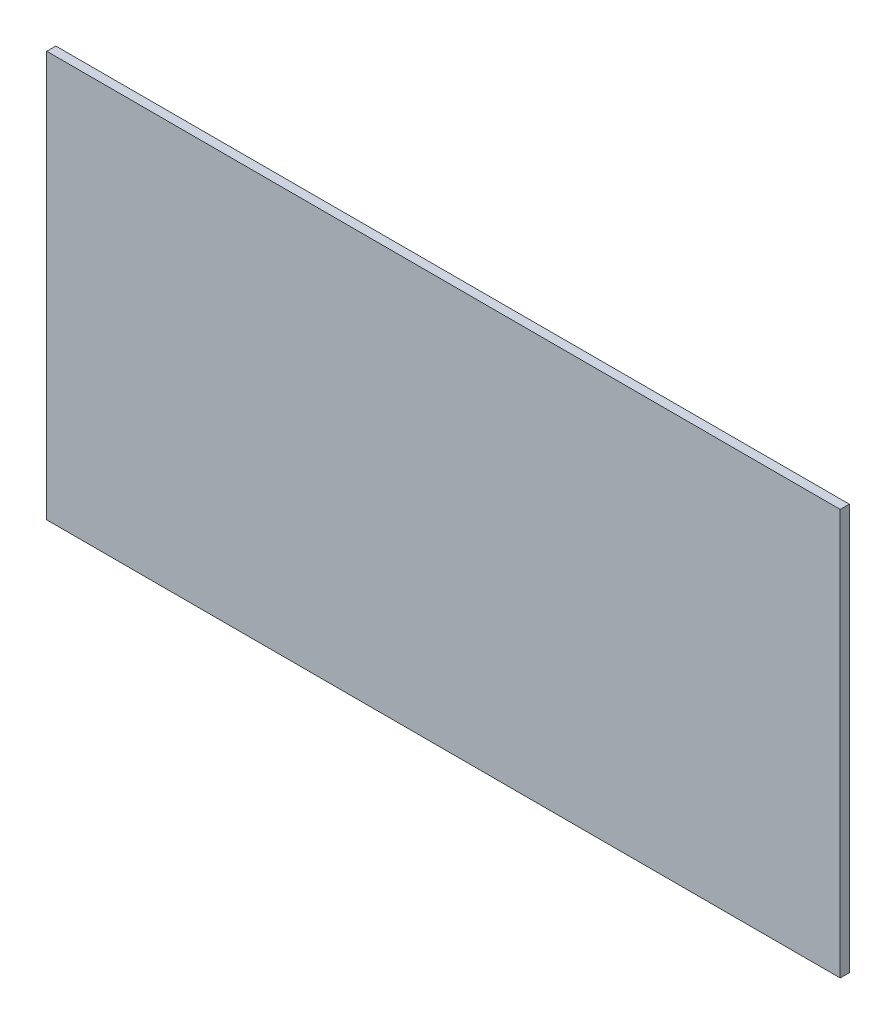
SolidWorks part; units mm, degrees
material "Chapa F.F 1020 - 1,5 mm"
ref_plane "Plano frontal" through (0, 0, 0) normal (0, 0, 1) x (1, 0, 0)
ref_plane "Plano superior" through (0, 0, 0) normal (0, 1, 0) x (1, 0, 0)
ref_plane "Plano direito" through (0, 0, 0) normal (1, 0, 0) x (0, 0, -1)
sketch "Esboço1" plane through (0, 0, 0) normal (0, 0, 1) x (1, 0, 0)
  line L1 (-65.5, -33.5) -> (65.5, -33.5)
  line L2 (-65.5, -33.5) -> (-65.5, 33.5)
  line L3 (-65.5, 33.5) -> (65.5, 33.5)
  line L4 (65.5, -33.5) -> (65.5, 33.5)
  line L5 (-65.5, -33.5) -> (65.5, 33.5) construction
  line L6 (-65.5, 33.5) -> (65.5, -33.5) construction
  point P0 (0, 0)
  dimension "D1" = 131
  dimension "D2" = 67
extrude "Ressalto-extrusão1" add sketch "Esboço1" along normal blind 1.5
